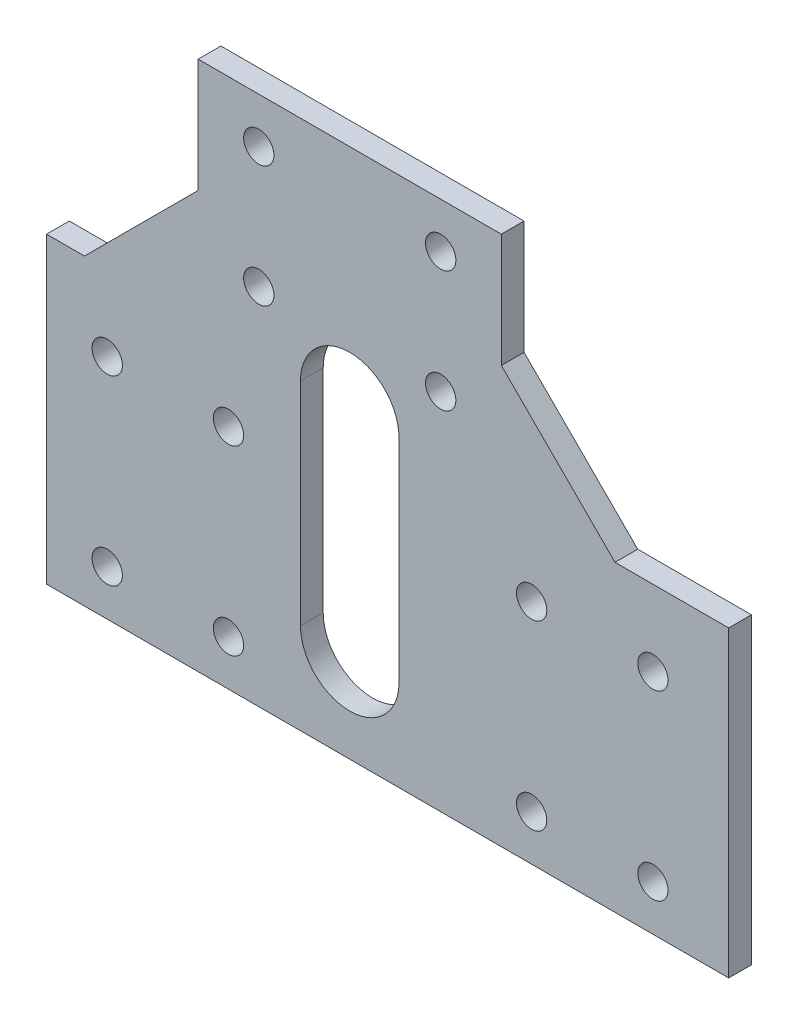
SolidWorks part; units mm, degrees
material "Thornel VCB-20 碳布"
ref_plane "前视基准面" through (0, 0, 0) normal (0, 0, 1) x (1, 0, 0)
ref_plane "上视基准面" through (0, 0, 0) normal (0, 1, 0) x (1, 0, 0)
ref_plane "右视基准面" through (0, 0, 0) normal (1, 0, 0) x (0, 0, -1)
other "Configuration Table"
sketch "草图1" plane through (0, 0, 0) normal (0, 0, 1) x (1, 0, 0)
  line L0 (0, 0) -> (0, 40)
  line L1 (0, 40) -> (5, 40)
  line L2 (5, 40) -> (20, 55)
  line L3 (20, 55) -> (20, 70)
  line L4 (20, 70) -> (60, 70)
  line L5 (60, 70) -> (60, 55)
  line L6 (60, 55) -> (75, 40)
  line L7 (75, 40) -> (90, 40)
  line L8 (90, 40) -> (90, 0)
  line L9 (90, 0) -> (0, 0)
  line L10 (60, 55) -> (20, 55) construction
  line L11 (20, 40) -> (5, 40) construction
  line L12 (20, 40) -> (20, 55) construction
  line L13 (60, 55) -> (60, 40) construction
  line L14 (60, 40) -> (75, 40)
  point P12 (104.9749, 61.2823)
  point P14 (52.5579, 40)
  point P15 (0, 39.5884)
  point P16 (17.4182, 37.2202)
  point P17 (53.1388, 53.5017)
  point P18 (28.7659, 40)
  dimension "D1" = 45
  dimension "D2" = 40
  dimension "D3" = 45
  dimension "D4" = 40
  dimension "D5" = 20
  dimension "D6" = 5
  dimension "D7" = 30
  dimension "D8" = 30
extrude "凸台-拉伸1" add sketch "草图1" along normal blind 3
sketch "草图2" plane through (0, 0, 3) normal (0, 0, 1) x (1, 0, 0)
  line L0 (0, 40) -> (90, 40) construction
  line L1 (28, 64) -> (28, 48) construction
  line L2 (28, 48) -> (52, 48) construction
  line L3 (52, 48) -> (52, 64) construction
  line L4 (52, 64) -> (28, 64) construction
  line L5 (20, 55) -> (20, 70) construction
  line L6 (20, 70) -> (60, 70) construction
  line L7 (8, 30) -> (80, 30) construction
  line L8 (80, 30) -> (80, 6) construction
  line L9 (80, 6) -> (8, 6) construction
  line L10 (8, 6) -> (8, 30) construction
  line L11 (0, 0) -> (0, 40) construction
  line L12 (90, 40) -> (90, 0) construction
  line L13 (90, 0) -> (0, 0) construction
  line L14 (40, 40) -> (40, 12) construction
  line L17 (46.5, 40) -> (46.5, 12)
  line L18 (33.5, 40) -> (33.5, 12)
  circle A0 centre (28, 64) radius 2
  circle A1 centre (28, 48) radius 2
  circle A2 centre (52, 64) radius 2
  circle A3 centre (52, 48) radius 2
  circle A4 centre (8, 30) radius 2
  circle A5 centre (24, 30) radius 2
  circle A6 centre (80, 30) radius 2
  circle A7 centre (64, 30) radius 2
  circle A8 centre (80, 6) radius 2
  circle A9 centre (64, 6) radius 2
  circle A10 centre (24, 6) radius 2
  circle A11 centre (8, 6) radius 2
  arc A15 (46.5, 40) -> (33.5, 40) centre (40, 40) ccw
  arc A16 (33.5, 12) -> (46.5, 12) centre (40, 12) ccw
  point P40 (40, 26)
  point P45 (42.1593, 26.9514)
  point P46 (42.3487, 12.5587)
  dimension "D1" = 4
  dimension "D6" = 4
  dimension "D15" = 12
  dimension "D16" = 6.5
  dimension "D2" = 24
  dimension "D3" = 8
  dimension "D4" = 6
  dimension "D5" = 16
  dimension "D7" = 8
  dimension "D8" = 10
  dimension "D9" = 16
  dimension "D10" = 40
  dimension "D11" = 16
  dimension "D12" = 40
  dimension "D13" = 6
  dimension "D14" = 10
  dimension "D17" = 28
  dimension "D18" = 12
extrude "切除-拉伸1" cut sketch "草图2" against normal blind 3
